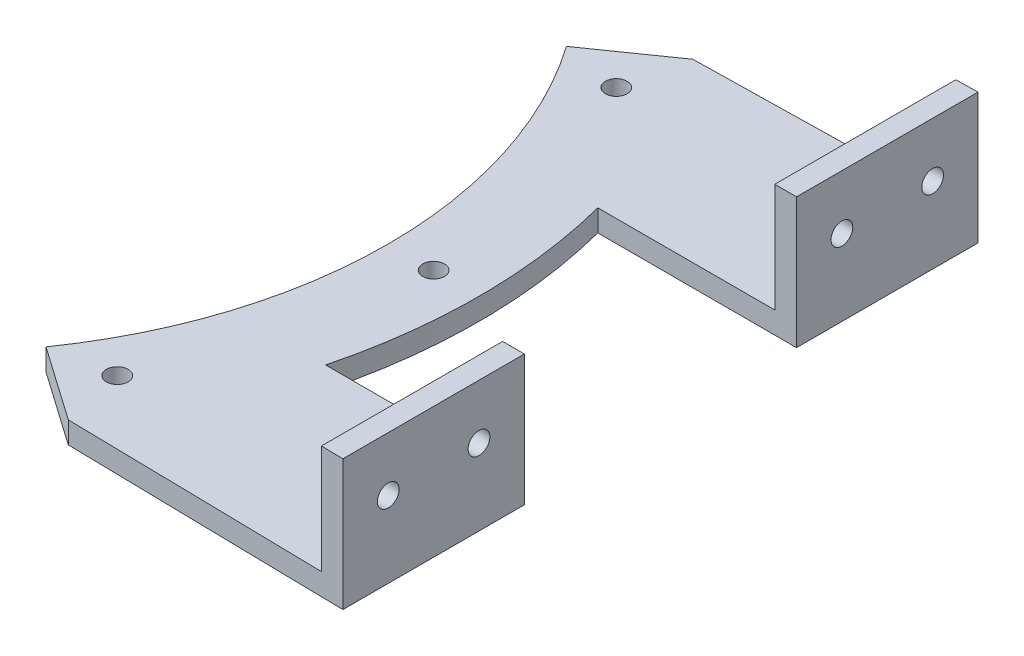
SolidWorks part; units mm, degrees
ref_plane "Front Plane" through (0, 0, 0) normal (0, 0, 1) x (1, 0, 0)
ref_plane "Top Plane" through (0, 0, 0) normal (0, 1, 0) x (1, 0, 0)
ref_plane "Right Plane" through (0, 0, 0) normal (1, 0, 0) x (0, 0, -1)
sketch "Sketch1" plane through (0, 0, 0) normal (0, 1, 0) x (1, 0, 0)
  line L0 (0, 0) -> (300, 0) construction
  line L1 (0, 0) -> (259.8076, 150) construction
  line L2 (0, 0) -> (259.8076, -150) construction
  line L3 (259.8076, 150) -> (259.8076, -150) construction
  line L5 (245.7456, 172.0729) -> (245.7456, -172.0729) construction
  line L11 (400, 175) -> (400, 75)
  line L12 (400, 75) -> (290.4738, 75)
  line L13 (400, -175) -> (400, -75)
  line L14 (400, -75) -> (290.4738, -75)
  line L15 (0, 0) -> (245.7456, 172.0729) construction
  line L16 (0, 0) -> (245.7456, -172.0729) construction
  line L17 (204.788, 143.3941) -> (245.7456, 172.0729)
  line L18 (204.788, -143.3941) -> (245.7456, -172.0729)
  line L21 (245.7456, 172.0729) -> (400, 175)
  line L22 (245.7456, -172.0729) -> (400, -175)
  arc A0 (204.788, -143.3941) -> (204.788, 143.3941) centre (0, 0) ccw
  arc A1 (245.7456, -172.0729) -> (245.7456, 172.0729) centre (0, 0) ccw construction
  circle A2 centre (0, 0) radius 275 construction
  circle A3 centre (238.157, -137.5) radius 6
  circle A4 centre (275, 0) radius 6
  circle A5 centre (238.157, 137.5) radius 6
  arc A8 (290.4738, -75) -> (290.4738, 75) centre (0, 0) ccw
  dimension "D4" = 550
  dimension "D1" = 600
  dimension "D2" = 500
  dimension "D5" = 12
  dimension "D3" = 60
  dimension "D6" = 100
  dimension "D7" = 100
  dimension "D8" = 400
  dimension "D9" = 70
  dimension "D10" = 350
extrude "Boss-Extrude2" add sketch "Sketch1" along normal blind 12
sketch "Sketch2" plane through (0, 12, 0) normal (0, 1, 0) x (1, 0, 0)
  line L4 (400, 75) -> (400, 175)
  line L5 (400, 75) -> (388.0022, 75)
  line L7 (388.0022, 75) -> (388.0022, 174.7723)
  line L11 (400, -175) -> (400, -75)
  line L13 (400, -75) -> (388.0022, -75)
  line L15 (400, -75) -> (290.4738, -75) construction
  line L16 (400, -175) -> (400, -75) construction
  line L17 (388.0022, -75) -> (388.0022, -174.7723)
  line L18 (245.7456, -172.0729) -> (400, -175) construction
  line L19 (388.0022, -174.7723) -> (400, -175)
  line L20 (400, 175) -> (245.7456, 172.0729) construction
  line L21 (400, 175) -> (388.0022, 174.7723)
  dimension "D1" = 12
extrude "Boss-Extrude3" add sketch "Sketch2" along normal blind 60
sketch "Sketch3" plane through (388.0022, 0, 0) normal (-1, 0, 0) x (0, 0, 1)
  line L0 (-174.7723, 42) -> (-75, 42) construction
  line L2 (-75, 72) -> (-75, 12) construction
  line L3 (75, 42) -> (174.7723, 42) construction
  line L6 (-174.7723, 72) -> (-174.7723, 12) construction
  line L7 (-125, 72) -> (-125, 12) construction
  line L10 (125, 12) -> (125, 72) construction
  line L13 (174.7723, 72) -> (174.7723, 12) construction
  line L14 (75, 72) -> (174.7723, 72) construction
  line L15 (75, 12) -> (174.7723, 12) construction
  line L16 (75, 72) -> (75, 12) construction
  circle A0 centre (-150, 42) radius 6
  circle A1 centre (-100, 42) radius 6
  circle A2 centre (100, 42) radius 6
  circle A3 centre (150, 42) radius 6
  dimension "D1" = 12
  dimension "D2" = 25
  dimension "D3" = 25
  dimension "D4" = 25
  dimension "D5" = 25
  dimension "D6" = 125
  dimension "D7" = 125
extrude "Cut-Extrude1" cut sketch "Sketch3" against normal through all
equation "\"mbtOD\" = 850"
equation "\"mbtT\" = 6"
equation "\"mbtL\" = 1500"
equation "\"mbtFlangeOD\" = 950"
equation "\"mbtFlangeT\" = 12"
equation "\"mbtFlangeBoltCircleDia\" = 650"
equation "\"mbtFlangeHoleDia\" = 12"
equation "\"mbtOringSize\" = 10 "
equation "\"mbtOringDia\" = 620"
equation "\"mbtWidth\" = 2250"
equation "\"skiWidth\" = 1250"
equation "\"mbtCapL\" = 500"
equation "\"vbtRearOD\" = 500"
equation "\"vbtRearT\" = 6.25"
equation "\"vbtRearFlangeOD\" = 600"
equation "\"vbtRearFlangeT\" = 12"
equation "\"vbtRearBoltHoleDia\" = 12"
equation "\"vbtFrontOD\" = 440"
equation "\"vbtFrontT\" = 25"
equation "\"vbtFrontFlangeOD\" = 500"
equation "\"vbtFrontFlangeT\" = 12"
equation "\"vbtFrontBoltHoleDia\" = 12"
equation "\"D4@Sketch1\"=(\"vbtRearOD\"+\"vbtRearFlangeOD\")/2"
equation "\"D1@Sketch1\"=\"vbtRearFlangeOD\""
equation "\"D2@Sketch1\"=\"vbtRearOD\""
equation "\"D5@Sketch1\"=\"vbtRearBoltHoleDia\""
equation "\"D8@Sketch1\"=\"vbtRearFlangeOD\"/2+100mm"
equation "\"D1@Boss-Extrude2\"=\"vbtRearFlangeT\""
equation "\"D1@Sketch2\"=\"vbtRearFlangeT\""
